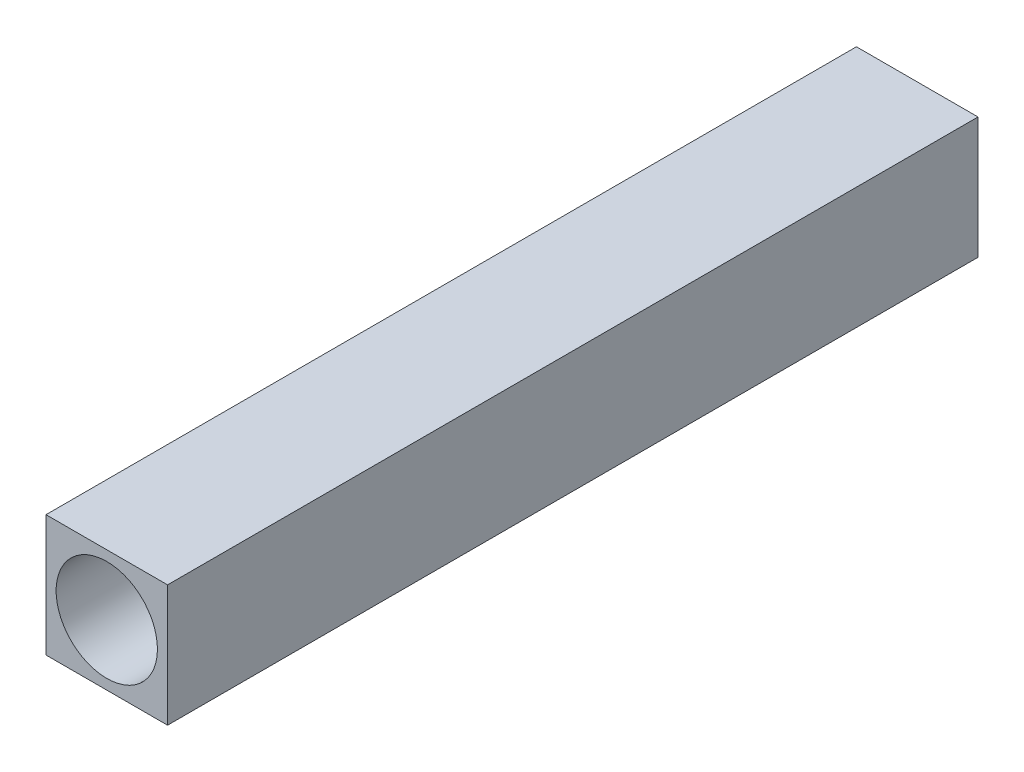
SolidWorks part; units mm, degrees
material "Custom Plastic"
ref_plane "Front Plane" through (0, 0, 0) normal (0, 0, 1) x (1, 0, 0)
ref_plane "Top Plane" through (0, 0, 0) normal (0, 1, 0) x (1, 0, 0)
ref_plane "Right Plane" through (0, 0, 0) normal (1, 0, 0) x (0, 0, -1)
other "Configuration Table"
sketch "Sketch1" plane through (0, 0, 0) normal (0, 0, 1) x (1, 0, 0)
  line L1 (-15, -15) -> (15, -15)
  line L2 (-15, -15) -> (-15, 15)
  line L3 (-15, 15) -> (15, 15)
  line L4 (15, -15) -> (15, 15)
  line L5 (-15, -15) -> (15, 15) construction
  line L6 (-15, 15) -> (15, -15) construction
  circle A0 centre (0, 0) radius 12.5
  dimension "D1" = 25
  dimension "D2" = 30
extrude "Boss-Extrude1" add sketch "Sketch1" along normal mid plane 200
